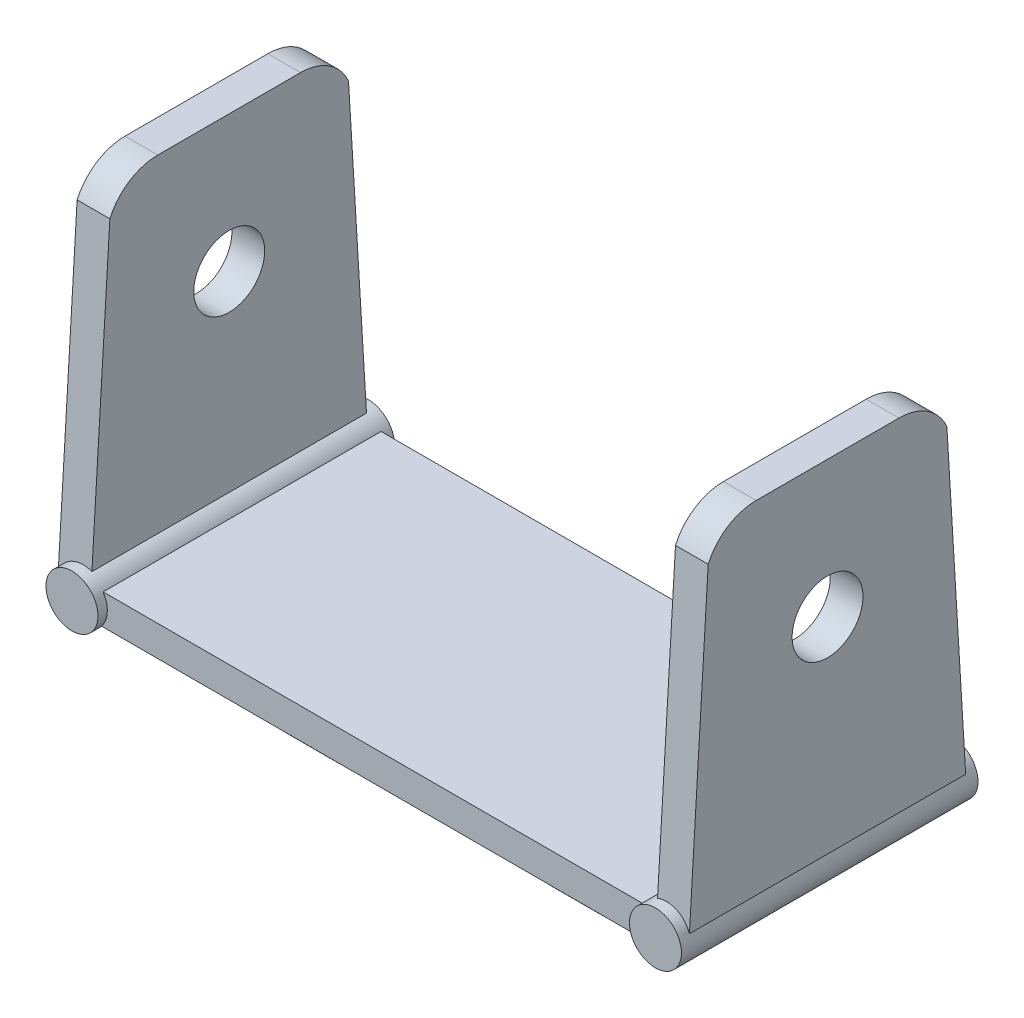
SolidWorks part; units mm, degrees
ref_plane "Front Plane" through (0, 0, 0) normal (0, 0, 1) x (1, 0, 0)
ref_plane "Top Plane" through (0, 0, 0) normal (0, 1, 0) x (1, 0, 0)
ref_plane "Right Plane" through (0, 0, 0) normal (1, 0, 0) x (0, 0, -1)
ref_plane "Plane1" through (127.1201, 0, 0) normal (1, 0, 0) x (0, 0, -1)
ref_plane "Plane2" through (0, 0, 66.6473) normal (0, 0, 1) x (1, 0, 0)
ref_plane "Plane3" through (47.4017, 0, 0) normal (1, 0, 0) x (0, 0, -1)
sketch "Sketch1" plane through (0, 0, 0) normal (0, 1, 0) x (1, 0, 0)
  line L0 (0, -62.4526) -> (0, 62.4526) construction
  line L1 (-126.6506, 62.4526) -> (126.6506, 62.4526)
  line L2 (-126.6506, 62.4526) -> (-126.6506, -62.4526)
  line L3 (-126.6506, -62.4526) -> (126.6506, -62.4526)
  line L4 (126.6506, 62.4526) -> (126.6506, -62.4526)
  dimension "D1" = 253.3012
  dimension "D2" = 124.9053
extrude "Boss-Extrude1" add sketch "Sketch1" along normal blind 13.7043
sketch "Sketch3" plane through (0, 0, 66.6473) normal (0, 0, 1) x (1, 0, 0)
  circle A0 centre (131.1274, 7.3386) radius 11.6853
  dimension "D3" = 23.3705
  dimension "D1" = 131.1274
  dimension "D2" = 7.3386
extrude "Boss-Extrude6" add sketch "Sketch3" against normal blind 133.2946
sketch "Sketch4" plane through (47.4017, 0, 0) normal (1, 0, 0) x (0, 0, -1)
  line L0 (-44.2166, 0) -> (44.2166, 0)
  arc A0 (-44.2166, 0) -> (44.2166, 0) centre (0, 0) ccw
  circle A1 centre (0, -19.0574) radius 13.9352
  dimension "D1" = 44.2166
  dimension "D2" = 27.8704
  dimension "D3" = 19.0574
extrude "Boss-Extrude7" add sketch "Sketch4" along normal blind 24.0612
sketch "Sketch2" plane through (127.1201, 0, 0) normal (1, 0, 0) x (0, 0, -1)
  line L0 (-62.4903, 5.3881) -> (62.4903, 5.3881)
  line L1 (62.4903, 5.3881) -> (53.6388, 151.6243)
  line L2 (0, 0) -> (0, 33.1654) construction
  line L3 (-62.4903, 5.3881) -> (-53.6388, 151.6243)
  line L4 (-32.0826, 165.6842) -> (32.0826, 165.6842)
  line L5 (-53.6388, 151.6243) -> (53.6388, 151.6243) construction
  arc A0 (-53.6388, 151.6243) -> (-32.0826, 165.6842) centre (-32.0826, 142.1296) cw
  arc A1 (32.0826, 165.6842) -> (53.6388, 151.6243) centre (32.0826, 142.1296) cw
  circle A2 centre (0, 104.3544) radius 15.9424
  point P4 (0, 5.3881)
  point P10 (0, 165.6842)
  point P11 (0, 151.6243)
  dimension "D7" = 31.8849
  dimension "D1" = 124.9807
  dimension "D2" = 5.3881
  dimension "D3" = 151.6243
  dimension "D4" = 165.6842
  dimension "D5" = 64.1652
  dimension "D6" = 107.2777
  dimension "D8" = 104.3544
extrude "Boss-Extrude8" add sketch "Sketch2" along normal blind 14.7132
mirror "Mirror5" about plane through (0, 0, 0) normal (1, 0, 0) of "Boss-Extrude8", "Boss-Extrude6", "Boss-Extrude7"
